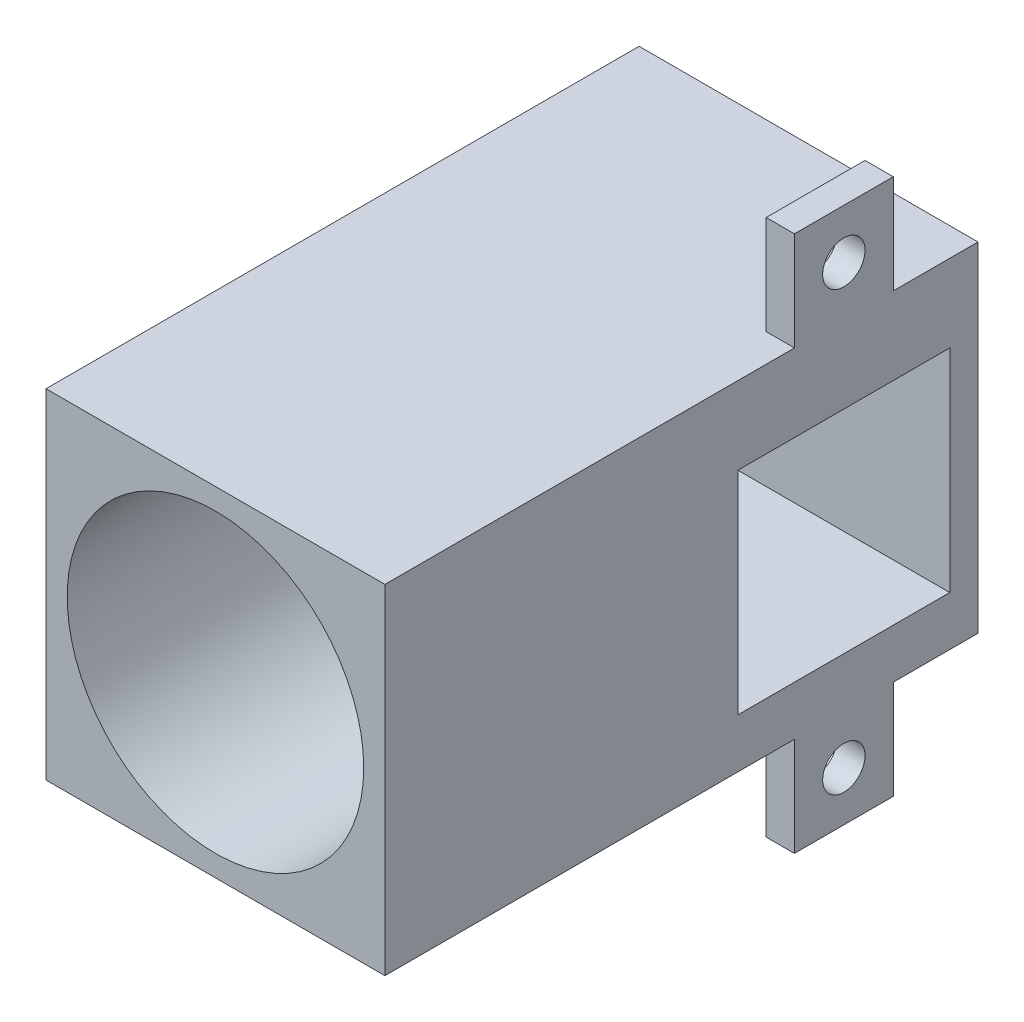
SolidWorks part; units mm, degrees
ref_plane "Спереди" through (0, 0, 0) normal (0, 0, 1) x (1, 0, 0)
ref_plane "Сверху" through (0, 0, 0) normal (0, 1, 0) x (1, 0, 0)
ref_plane "Справа" through (0, 0, 0) normal (1, 0, 0) x (0, 0, -1)
sketch "Эскиз1" plane through (0, 0, 0) normal (0, 0, 1) x (1, 0, 0)
  line L1 (12, 12) -> (-12, 12)
  line L2 (-12, 12) -> (-12, -12)
  line L3 (-12, -12) -> (12, -12)
  line L4 (12, -12) -> (12, 12)
  dimension "D1" = 24
  dimension "D2" = 24
  dimension "D3" = 12
  dimension "D4" = 12
extrude "Бобышка-Вытянуть1" add sketch "Эскиз1" along normal blind 42
sketch "Эскиз3" plane through (0, 0, 42) normal (0, 0, 1) x (1, 0, 0)
  circle A0 centre (0, 0) radius 10.5
extrude "Вырез-Вытянуть1" cut sketch "Эскиз3" against normal blind 20
sketch "Эскиз4" plane through (0, 0, 22) normal (0, 0, 1) x (1, 0, 0)
  line L1 (8.5, 8.5) -> (-8.5, 8.5)
  line L2 (8.5, 8.5) -> (8.5, -8.5)
  line L3 (8.5, -8.5) -> (-8.5, -8.5)
  line L4 (-8.5, 8.5) -> (-8.5, -8.5)
  line L5 (8.5, 8.5) -> (-8.5, -8.5) construction
  line L6 (8.5, -8.5) -> (-8.5, 8.5) construction
  point P0 (0, 0)
extrude "Вырез-Вытянуть2" cut sketch "Эскиз4" against normal blind 20
sketch "Эскиз5" plane through (12, 0, 0) normal (1, 0, 0) x (0, 0, -1)
  line L0 (-42, 12) -> (0, 12) construction
  line L1 (-2, -8.5) -> (-17, -8.5)
  line L7 (-2, 6.5) -> (-2, -8.5)
  line L8 (-17, -8.5) -> (-17, 6.5)
  line L9 (-17, 6.5) -> (-2, 6.5)
  line L11 (0, -12) -> (0, 12) construction
  point P9 (-2, 2.4245)
  point P10 (-2, 6.2609)
  dimension "D1" = 15
  dimension "D2" = 15
  dimension "D3" = 5.5
  dimension "D4" = 2
extrude "Вырез-Вытянуть5" cut sketch "Эскиз5" against normal through all
sketch "Эскиз6" plane through (12, 0, 0) normal (1, 0, 0) x (0, 0, -1)
  line L2 (-42, 12) -> (0, 12) construction
  line L3 (-6, 12) -> (-13, 12)
  line L5 (-6, 12) -> (-6, 19)
  line L6 (-6, 19) -> (-13, 19)
  line L7 (-13, 19) -> (-13, 12)
  line L12 (-42, -12) -> (0, -12) construction
  line L14 (-13, -12) -> (-13, -19)
  line L15 (-13, -19) -> (-6, -19)
  line L16 (-6, -19) -> (-6, -12)
  line L17 (-6, -12) -> (-13, -12)
  circle A0 centre (-9.5, -15.5) radius 1.5
  circle A1 centre (-9.5, 15.5) radius 1.5
extrude "Бобышка-Вытянуть2" add sketch "Эскиз6" against normal blind 2
